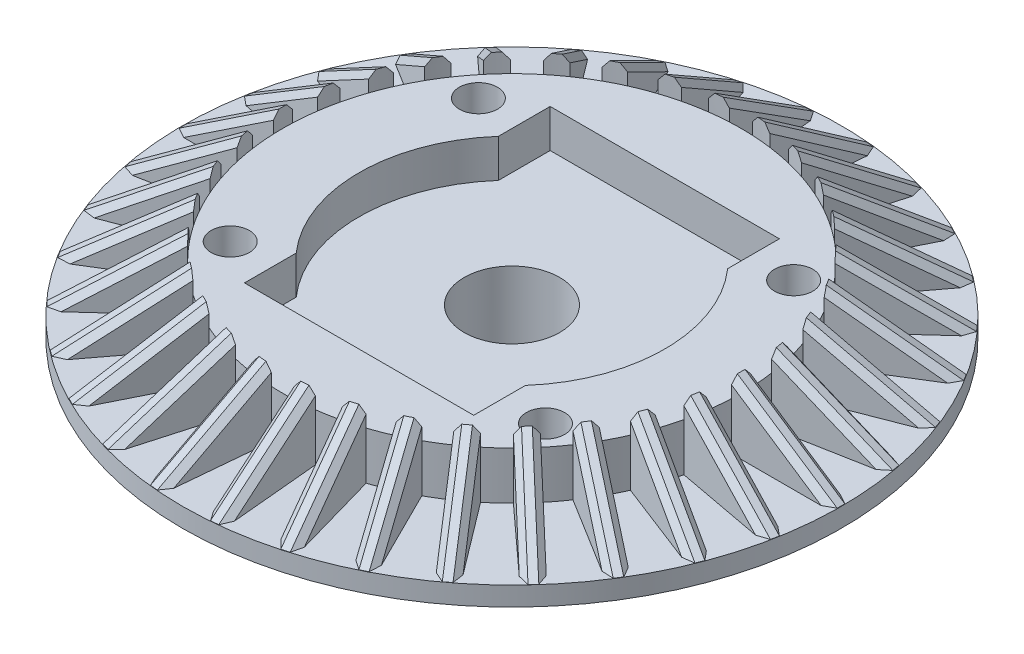
SolidWorks part; units mm, degrees
material "Cast Alloy Steel"
ref_plane "Front" through (0, 0, 0) normal (0, 0, 1) x (1, 0, 0)
ref_plane "Top" through (0, 0, 0) normal (0, 1, 0) x (1, 0, 0)
ref_plane "Right" through (0, 0, 0) normal (1, 0, 0) x (0, 0, -1)
sketch "Sketch1" plane through (0, 0, 0) normal (0, 1, 0) x (1, 0, 0)
  circle A0 centre (0, 0) radius 17.25
  dimension "D1" = 34.5
extrude "Boss-Extrude1" add sketch "Sketch1" along normal blind 1
sketch "Sketch9" plane through (0, 1, 0) normal (0, 1, 0) x (1, 0, 0)
  circle A0 centre (0, 0) radius 12
  dimension "D1" = 24
extrude "Boss-Extrude3" add sketch "Sketch9" along normal blind 3.5
sketch "Sketch15" plane through (0, 0, 0) normal (0, 0, 1) x (1, 0, 0)
  line L0 (-12, 4.4815) -> (-17.2246, 1)
  line L1 (-12, 4.5) -> (-12, 1) construction
  line L2 (17.25, 1) -> (-17.25, 1) construction
rib "Rib4" sketch "Sketch15" sketch "Sketch15" thickness 1 extrusion direction parallel to sketch draft on no parameters "D1"=1
chamfer "Chamfer4" distance 0.3 angle 45 2 edges at (-14.6071, 2.7442, -0.5) (-14.6071, 2.7442, 0.5)
pattern_circular "CirPattern4" count 34 over 360 about axis through (0, 0, 0) along (0, 1, 0) of "Chamfer4", "Rib4"
sketch "Sketch16" plane through (0, 4.5, 0) normal (0, 1, 0) x (1, 0, 0)
  circle A0 centre (0, 0) radius 12
extrude "Cut-Extrude5" cut sketch "Sketch16" against normal blind 1
sketch "Sketch17" plane through (0, 3.5, 0) normal (0, 1, 0) x (1, 0, 0)
  line L1 (-8.25, -6.4952) -> (8.25, -6.4952) construction
  line L2 (-8.25, -6.4952) -> (-8.25, 6.4952) construction
  line L3 (-8.25, 6.4952) -> (8.25, 6.4952) construction
  line L4 (8.25, -6.4952) -> (8.25, 6.4952) construction
  line L5 (-8.25, -6.4952) -> (8.25, 6.4952) construction
  line L6 (-8.25, 6.4952) -> (8.25, -6.4952) construction
  circle A0 centre (0, 0) radius 10.5 construction
  circle A1 centre (-8.25, 6.4952) radius 1
  dimension "D1" = 21
  dimension "D3" = 2
  dimension "D2" = 16.5
extrude "Cut-Extrude6" cut sketch "Sketch17" against normal through all
mirror "Mirror3" about plane through (0, 0, 0) normal (1, 0, 0) of "Cut-Extrude6"
mirror "Mirror4" about plane through (0, 0, 0) normal (0, 0, 1) of "Mirror3", "Cut-Extrude6"
sketch "Sketch18" plane through (0, 3.5, 0) normal (0, 1, 0) x (1, 0, 0)
  line L1 (-6, -8) -> (6, -8)
  line L2 (-6, -8) -> (-6, -5.2915)
  line L3 (-6, 8) -> (6, 8)
  line L4 (6, -8) -> (6, -5.2915)
  line L7 (-6, 5.2915) -> (-6, 8)
  line L9 (6, 5.2915) -> (6, 8)
  arc A0 (-6, 5.2915) -> (-6, -5.2915) centre (0, 0) ccw
  arc A1 (6, -5.2915) -> (6, 5.2915) centre (0, 0) ccw
  point P0 (0, 0)
  dimension "D1" = 12
  dimension "D2" = 16
extrude "Cut-Extrude7" cut sketch "Sketch18" against normal blind 2
sketch "Sketch19" plane through (0, 0, 0) normal (0, -1, 0) x (1, 0, 0)
  circle A0 centre (0, 0) radius 6
  dimension "D1" = 12
extrude "Boss-Extrude5" add sketch "Sketch19" along normal blind 0.5
sketch "Sketch20" plane through (0, -0.5, 0) normal (0, -1, 0) x (1, 0, 0)
  circle A0 centre (0, 0) radius 4
  dimension "D1" = 8
extrude "Boss-Extrude6" add sketch "Sketch20" along normal blind 4
sketch "Sketch22" plane through (0, -4.5, 0) normal (0, -1, 0) x (1, 0, 0)
  circle A0 centre (0, 0) radius 2.5
  dimension "D1" = 5
extrude "Cut-Extrude8" cut sketch "Sketch22" against normal through all
sketch "Sketch23" plane through (0, 0, 0) normal (0, 1, 0) x (1, 0, 0)
  circle A0 centre (8.25, -6.4952) radius 2
  dimension "D1" = 4
extrude "Cut-Extrude9" cut sketch "Sketch23" along normal blind 0.8
mirror "Mirror5" about plane through (0, 0, 0) normal (1, 0, 0) of "Cut-Extrude9"
mirror "Mirror6" about plane through (0, 0, 0) normal (0, 0, 1) of "Mirror5", "Cut-Extrude9"
